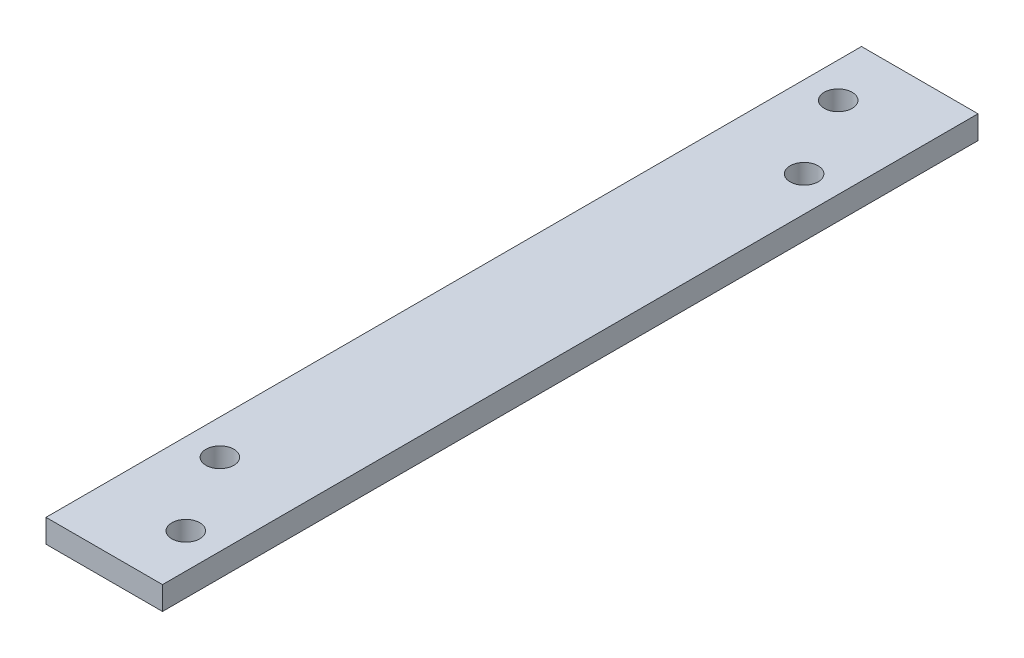
SolidWorks part; units mm, degrees
ref_plane "Front Plane" through (0, 0, 0) normal (0, 0, 1) x (1, 0, 0)
ref_plane "Top Plane" through (0, 0, 0) normal (0, 1, 0) x (1, 0, 0)
ref_plane "Right Plane" through (0, 0, 0) normal (1, 0, 0) x (0, 0, -1)
sketch "Sketch1" plane through (0, 0, 0) normal (0, 1, 0) x (1, 0, 0)
  line L0 (0, 44.45) -> (12.7, 44.45) construction
  line L1 (0, 0) -> (12.7, 0)
  line L2 (0, 0) -> (0, 88.9)
  line L3 (0, 88.9) -> (12.7, 88.9)
  line L4 (12.7, 0) -> (12.7, 88.9)
  circle A0 centre (3.81, 82.55) radius 1.524
  circle A1 centre (8.89, 73.7512) radius 1.524
  circle A4 centre (3.81, 15.1488) radius 1.524
  circle A5 centre (8.89, 6.35) radius 1.524
  point P9 (6.35, 44.45)
  point P18 (6.3484, 44.4817)
  point P20 (6.35, 44.45)
  dimension "D3" = 3.048
  dimension "D4" = 3.048
  dimension "D1" = 12.7
  dimension "D2" = 88.9
  dimension "D5" = 10.16
  dimension "D6" = 3.81
  dimension "D7" = 8.89
  dimension "D8" = 6.35
  dimension "D9" = 2
extrude "Boss-Extrude1" add sketch "Sketch1" along normal blind 2.54
